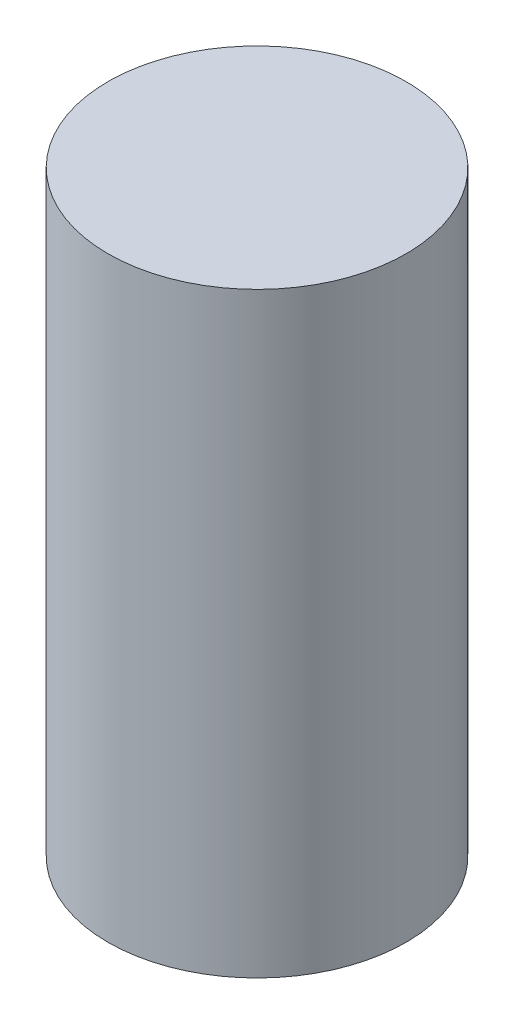
SolidWorks part; units mm, degrees
ref_plane "Спереди" through (0, 0, 0) normal (0, 0, 1) x (1, 0, 0)
ref_plane "Сверху" through (0, 0, 0) normal (0, 1, 0) x (1, 0, 0)
ref_plane "Справа" through (0, 0, 0) normal (1, 0, 0) x (0, 0, -1)
sketch "Эскиз1" plane through (0, 0, 0) normal (0, 1, 0) x (1, 0, 0)
  circle A0 centre (0, 0) radius 12.5
extrude "Вытянуть1" add sketch "Эскиз1" along normal blind 50
